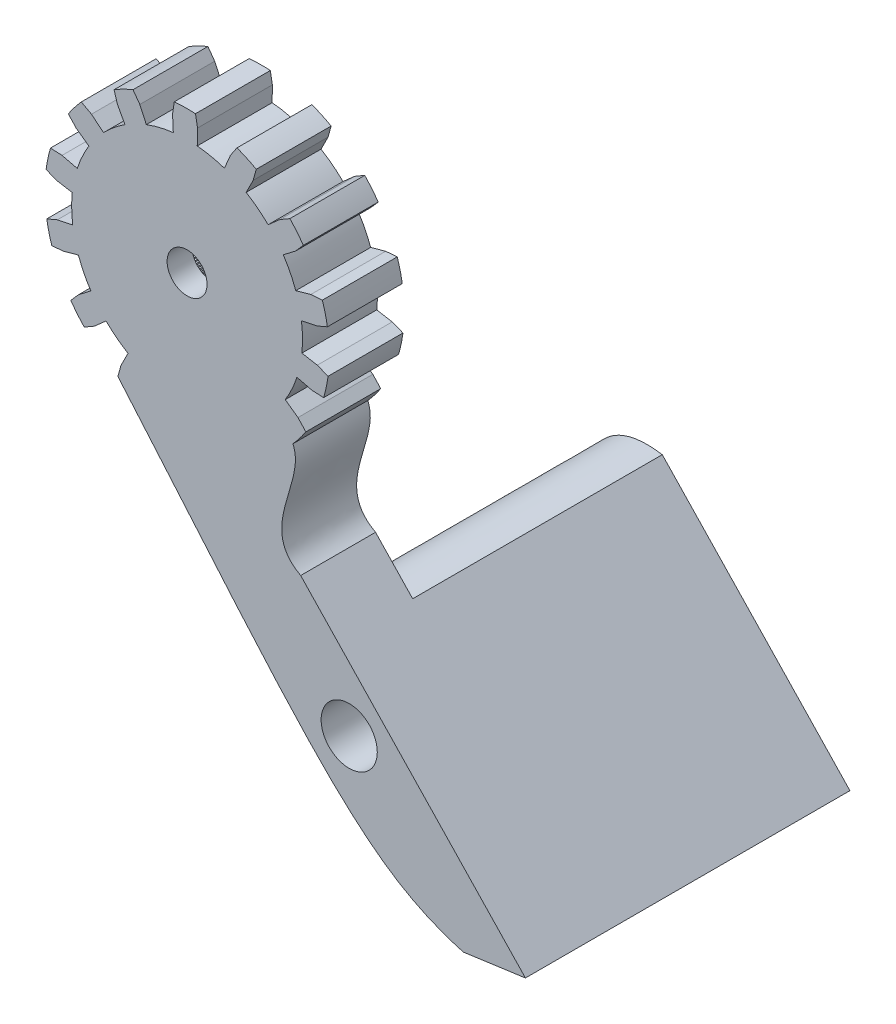
SolidWorks part; units mm, degrees
ref_plane "Front Plane" through (0, 0, 0) normal (0, 0, 1) x (1, 0, 0)
ref_plane "Top Plane" through (0, 0, 0) normal (0, 1, 0) x (1, 0, 0)
ref_plane "Right Plane" through (0, 0, 0) normal (1, 0, 0) x (0, 0, -1)
sketch "Sketch2" plane through (0, 0, 0) normal (0, 0, 1) x (1, 0, 0)
  line L0 (11.1946, 10) -> (11.1946, 10.6054) construction
  line L669 (17.6878, 7.31) -> (18.6279, 8.138)
  line L670 (18.6279, 8.138) -> (19.4304, 8.6044)
  line L671 (21.6272, -0.4657) -> (22.4922, -0.8024)
  line L672 (20.3937, -0.247) -> (21.6272, -0.4657)
  line L673 (20.3589, 1.9784) -> (21.5849, 2.2356)
  line L674 (21.5849, 2.2356) -> (22.439, 2.5991)
  line L675 (21.1094, 4.1784) -> (22.0348, 4.2505)
  line L676 (19.9032, 3.8403) -> (21.1094, 4.1784)
  line L677 (18.9062, 5.8303) -> (19.8993, 6.5939)
  line L678 (19.8993, 6.5939) -> (20.511, 7.292)
  line L679 (14.4587, -7.9329) -> (14.9822, -9.071)
  line L680 (14.9822, -9.071) -> (15.5266, -9.8227)
  line L681 (16.7705, -8.175) -> (17.0467, -9.0612)
  line L682 (16.1724, -7.0743) -> (16.7705, -8.175)
  line L683 (17.8907, -5.6595) -> (18.8561, -6.4578)
  line L684 (18.8561, -6.4578) -> (19.6729, -6.8988)
  line L685 (20.0786, -4.8746) -> (20.7119, -5.5532)
  line L686 (19.0622, -4.1424) -> (20.0786, -4.8746)
  line L687 (19.9964, -2.1222) -> (21.2126, -2.4225)
  line L688 (21.2126, -2.4225) -> (22.1398, -2.4655)
  line L689 (3.4829, -4.3861) -> (2.4899, -5.1497)
  line L690 (2.4899, -5.1497) -> (1.8781, -5.8478)
  line L691 (3.7613, -6.6939) -> (2.9588, -7.1603)
  line L692 (4.7013, -5.8658) -> (3.7613, -6.6939)
  line L693 (6.463, -7.2262) -> (5.8996, -8.3451)
  line L694 (5.8996, -8.3451) -> (5.6513, -9.2394)
  line L695 (7.7151, -9.1846) -> (7.1944, -9.953)
  line L696 (8.2027, -8.0307) -> (7.7151, -9.1846)
  line L697 (10.3802, -8.492) -> (10.3581, -9.7445)
  line L698 (10.3581, -9.7445) -> (10.5224, -10.6581)
  line L699 (12.358, -9.7133) -> (12.2223, -10.6315)
  line L700 (12.2967, -8.462) -> (12.358, -9.7133)
  line L701 (2.3105, 6.3188) -> (1.6772, 6.9974)
  line L702 (3.327, 5.5866) -> (2.3105, 6.3188)
  line L703 (2.3927, 3.5664) -> (1.1765, 3.8667)
  line L704 (1.1765, 3.8667) -> (0.2493, 3.9097)
  line L705 (0.762, 1.9099) -> (-0.103, 2.2465)
  line L706 (1.9955, 1.6912) -> (0.762, 1.9099)
  line L707 (2.0303, -0.5343) -> (0.8042, -0.7914)
  line L708 (0.8042, -0.7914) -> (-0.0498, -1.1549)
  line L709 (1.2798, -2.7343) -> (0.3543, -2.8063)
  line L710 (2.486, -2.3961) -> (1.2798, -2.7343)
  line L711 (12.009, 9.9362) -> (12.0311, 11.1887)
  line L712 (12.0311, 11.1887) -> (11.8667, 12.1023)
  line L713 (10.0311, 11.1574) -> (10.1668, 12.0757)
  line L714 (10.0924, 9.9062) -> (10.0311, 11.1574)
  line L715 (7.9305, 9.377) -> (7.4069, 10.5151)
  line L716 (7.4069, 10.5151) -> (6.8625, 11.2669)
  line L717 (5.6186, 9.6192) -> (5.3425, 10.5054)
  line L718 (6.2167, 8.5185) -> (5.6186, 9.6192)
  line L719 (4.4985, 7.1037) -> (3.533, 7.9019)
  line L720 (3.533, 7.9019) -> (2.7163, 8.343)
  line L721 (15.9262, 8.6703) -> (16.4895, 9.7892)
  line L722 (16.4895, 9.7892) -> (16.7378, 10.6836)
  line L723 (14.6741, 10.6288) -> (15.1948, 11.3972)
  line L724 (14.1864, 9.4749) -> (14.6741, 10.6288)
  arc A141 (20.511, 7.292) -> (19.4304, 8.6044) centre (11.1946, 0.7221) ccw
  arc A145 (17.6878, 7.31) -> (15.9262, 8.6703) centre (11.1946, 0.7221) ccw
  arc A149 (22.439, 2.5991) -> (22.0348, 4.2505) centre (11.1946, 0.7221) ccw
  arc A151 (22.1398, -2.4655) -> (22.4922, -0.8024) centre (11.1946, 0.7221) ccw
  arc A152 (19.6729, -6.8988) -> (20.7119, -5.5532) centre (11.1946, 0.7221) ccw
  arc A153 (15.5266, -9.8227) -> (17.0467, -9.0612) centre (11.1946, 0.7221) ccw
  arc A154 (10.5224, -10.6581) -> (12.2223, -10.6315) centre (11.1946, 0.7221) ccw
  arc A155 (5.6513, -9.2394) -> (7.1944, -9.953) centre (11.1946, 0.7221) ccw
  arc A156 (1.8781, -5.8478) -> (2.9588, -7.1603) centre (11.1946, 0.7221) ccw
  arc A157 (-0.0498, -1.1549) -> (0.3543, -2.8063) centre (11.1946, 0.7221) ccw
  arc A158 (0.2493, 3.9097) -> (-0.103, 2.2465) centre (11.1946, 0.7221) ccw
  arc A159 (2.7163, 8.343) -> (1.6772, 6.9974) centre (11.1946, 0.7221) ccw
  arc A160 (6.8625, 11.2669) -> (5.3425, 10.5054) centre (11.1946, 0.7221) ccw
  arc A161 (11.8667, 12.1023) -> (10.1668, 12.0757) centre (11.1946, 0.7221) ccw
  arc A162 (16.7378, 10.6836) -> (15.1948, 11.3972) centre (11.1946, 0.7221) ccw
  arc A163 (19.9032, 3.8403) -> (18.9062, 5.8303) centre (11.1946, 0.7221) ccw
  arc A164 (20.3937, -0.247) -> (20.3589, 1.9784) centre (11.1946, 0.7221) ccw
  arc A165 (19.0622, -4.1424) -> (19.9964, -2.1222) centre (11.1946, 0.7221) ccw
  arc A166 (16.1724, -7.0743) -> (17.8907, -5.6595) centre (11.1946, 0.7221) ccw
  arc A167 (12.2967, -8.462) -> (14.4587, -7.9329) centre (11.1946, 0.7221) ccw
  arc A168 (8.2027, -8.0307) -> (10.3802, -8.492) centre (11.1946, 0.7221) ccw
  arc A169 (4.7013, -5.8658) -> (6.463, -7.2262) centre (11.1946, 0.7221) ccw
  arc A170 (2.486, -2.3961) -> (3.4829, -4.3861) centre (11.1946, 0.7221) ccw
  arc A171 (1.9955, 1.6912) -> (2.0303, -0.5343) centre (11.1946, 0.7221) ccw
  arc A172 (3.327, 5.5866) -> (2.3927, 3.5664) centre (11.1946, 0.7221) ccw
  arc A173 (6.2167, 8.5185) -> (4.4985, 7.1037) centre (11.1946, 0.7221) ccw
  arc A174 (10.0924, 9.9062) -> (7.9305, 9.377) centre (11.1946, 0.7221) ccw
  arc A175 (14.1864, 9.4749) -> (12.009, 9.9362) centre (11.1946, 0.7221) ccw
extrude "Boss-Extrude1" add sketch "Sketch2" against normal blind 4 and the other way blind 2
sketch "Sketch3" plane through (0, 0, 2) normal (0, 0, 1) x (1, 0, 0)
  circle A0 centre (11.1946, 0) radius 3.5
  dimension "D1" = 7
extrude "Boss-Extrude2" add sketch "Sketch3" against normal blind 2
sketch "Sketch4" plane through (0, 0, 2) normal (0, 0, 1) x (1, 0, 0)
  circle A0 centre (11.1946, 0.7221) radius 4.295 construction
sketch "Sketch5" plane through (0, 0, 2) normal (0, 0, 1) x (1, 0, 0)
  line L0 (10.0276, -11.444) -> (15.4878, -11.444) construction
  line L1 (4.4176, 11.5) -> (18.1778, 11.5) construction
  line L5 (20.2959, -15.7283) -> (38.3061, -34.6532)
  line L7 (33.3336, -35.343) -> (38.3061, -34.6532)
  line L25 (15.9262, 8.6703) -> (16.4895, 9.7892)
  line L35 (3.4829, -4.3861) -> (2.4899, -5.1497)
  line L45 (15.1948, 11.3972) -> (14.6741, 10.6288)
  line L55 (14.6741, 10.6288) -> (14.1864, 9.4749)
  line L98 (22.0348, 4.2505) -> (21.1094, 4.1784)
  line L102 (12.009, 9.9362) -> (12.0311, 11.1887)
  line L104 (14.9822, -9.071) -> (15.5266, -9.8227)
  line L105 (14.9822, -9.071) -> (15.5266, -9.8227)
  line L110 (2.4899, -5.1497) -> (1.8781, -5.8478)
  line L114 (5.8996, -8.3451) -> (5.6513, -9.2394)
  line L124 (2.3927, 3.5664) -> (1.1765, 3.8667)
  line L126 (1.1765, 3.8667) -> (0.2493, 3.9097)
  line L130 (0.8042, -0.7914) -> (-0.0498, -1.1549)
  line L140 (5.3425, 10.5054) -> (5.6186, 9.6192)
  line L146 (16.4895, 9.7892) -> (16.7378, 10.6836)
  line L153 (12.0311, 11.1887) -> (11.8667, 12.1023)
  line L157 (10.1668, 12.0757) -> (10.0311, 11.1574)
  line L161 (10.0311, 11.1574) -> (10.0924, 9.9062)
  line L196 (7.9305, 9.377) -> (7.4069, 10.5151)
  line L198 (7.4069, 10.5151) -> (6.8625, 11.2669)
  line L200 (5.6186, 9.6192) -> (6.2167, 8.5185)
  line L202 (4.4985, 7.1037) -> (3.533, 7.9019)
  line L204 (3.533, 7.9019) -> (2.7163, 8.343)
  line L206 (1.6772, 6.9974) -> (2.3105, 6.3188)
  line L208 (2.3105, 6.3188) -> (3.327, 5.5866)
  line L210 (-0.103, 2.2465) -> (0.762, 1.9099)
  line L212 (0.762, 1.9099) -> (1.9955, 1.6912)
  line L214 (2.0303, -0.5343) -> (0.8042, -0.7914)
  line L216 (0.3543, -2.8063) -> (1.2798, -2.7343)
  line L218 (1.2798, -2.7343) -> (2.486, -2.3961)
  line L220 (2.9588, -7.1603) -> (3.7613, -6.6939)
  line L222 (3.7613, -6.6939) -> (4.7013, -5.8658)
  line L224 (6.463, -7.2262) -> (5.8996, -8.3451)
  line L226 (7.1944, -9.953) -> (7.7151, -9.1846)
  line L227 (7.1944, -9.953) -> (7.7151, -9.1846)
  line L228 (7.7151, -9.1846) -> (8.2027, -8.0307)
  line L229 (7.7151, -9.1846) -> (8.2027, -8.0307)
  line L230 (10.3802, -8.492) -> (10.3581, -9.7445)
  line L231 (10.3802, -8.492) -> (10.3581, -9.7445)
  line L232 (10.3581, -9.7445) -> (10.5224, -10.6581)
  line L233 (10.3581, -9.7445) -> (10.5224, -10.6581)
  line L234 (12.2223, -10.6315) -> (12.358, -9.7133)
  line L235 (12.2223, -10.6315) -> (12.358, -9.7133)
  line L236 (12.358, -9.7133) -> (12.2967, -8.462)
  line L237 (12.358, -9.7133) -> (12.2967, -8.462)
  line L238 (14.4587, -7.9329) -> (14.9822, -9.071)
  line L239 (14.4587, -7.9329) -> (14.9822, -9.071)
  line L240 (17.0467, -9.0612) -> (16.7705, -8.175)
  line L241 (17.0467, -9.0612) -> (16.7705, -8.175)
  line L242 (16.7705, -8.175) -> (16.1724, -7.0743)
  line L243 (16.7705, -8.175) -> (16.1724, -7.0743)
  line L244 (17.8907, -5.6595) -> (18.8561, -6.4578)
  line L245 (17.8907, -5.6595) -> (18.8561, -6.4578)
  line L246 (18.8561, -6.4578) -> (19.6729, -6.8988)
  line L247 (18.8561, -6.4578) -> (19.6729, -6.8988)
  line L248 (20.7119, -5.5532) -> (20.0786, -4.8746)
  line L250 (20.0786, -4.8746) -> (19.0622, -4.1424)
  line L252 (19.9964, -2.1222) -> (21.2126, -2.4225)
  line L254 (21.2126, -2.4225) -> (22.1398, -2.4655)
  line L256 (22.4922, -0.8024) -> (21.6272, -0.4657)
  line L258 (21.6272, -0.4657) -> (20.3937, -0.247)
  line L260 (20.3589, 1.9784) -> (21.5849, 2.2356)
  line L262 (21.5849, 2.2356) -> (22.439, 2.5991)
  line L264 (21.1094, 4.1784) -> (19.9032, 3.8403)
  line L266 (18.9062, 5.8303) -> (19.8993, 6.5939)
  line L268 (19.8993, 6.5939) -> (20.511, 7.292)
  line L270 (19.4304, 8.6044) -> (18.6279, 8.138)
  line L272 (18.6279, 8.138) -> (17.6878, 7.31)
  arc A14 (17.6878, 7.31) -> (15.9262, 8.6703) centre (11.1946, 0.7221) ccw
  arc A36 (16.7378, 10.6836) -> (15.1948, 11.3972) centre (11.1946, 0.7221) ccw
  arc A44 (14.1864, 9.4749) -> (12.009, 9.9362) centre (11.1946, 0.7221) ccw
  arc A52 (11.8667, 12.1023) -> (10.1668, 12.0757) centre (11.1946, 0.7221) ccw
  arc A98 (10.0924, 9.9062) -> (7.9305, 9.377) centre (11.1946, 0.7221) ccw
  arc A100 (6.8625, 11.2669) -> (5.3425, 10.5054) centre (11.1946, 0.7221) ccw
  arc A102 (6.2167, 8.5185) -> (4.4985, 7.1037) centre (11.1946, 0.7221) ccw
  arc A104 (2.7163, 8.343) -> (1.6772, 6.9974) centre (11.1946, 0.7221) ccw
  arc A106 (3.327, 5.5866) -> (2.3927, 3.5664) centre (11.1946, 0.7221) ccw
  arc A108 (0.2493, 3.9097) -> (-0.103, 2.2465) centre (11.1946, 0.7221) ccw
  arc A110 (1.9955, 1.6912) -> (2.0303, -0.5343) centre (11.1946, 0.7221) ccw
  arc A112 (-0.0498, -1.1549) -> (0.3543, -2.8063) centre (11.1946, 0.7221) ccw
  arc A114 (2.486, -2.3961) -> (3.4829, -4.3861) centre (11.1946, 0.7221) ccw
  arc A116 (1.8781, -5.8478) -> (2.9588, -7.1603) centre (11.1946, 0.7221) ccw
  arc A118 (4.7013, -5.8658) -> (6.463, -7.2262) centre (11.1946, 0.7221) ccw
  arc A120 (5.6513, -9.2394) -> (7.1944, -9.953) centre (11.1946, 0.7221) ccw
  arc A121 (5.6513, -9.2394) -> (7.1944, -9.953) centre (11.1946, 0.7221) ccw
  arc A122 (8.2027, -8.0307) -> (10.3802, -8.492) centre (11.1946, 0.7221) ccw
  arc A123 (8.2027, -8.0307) -> (10.3802, -8.492) centre (11.1946, 0.7221) ccw
  arc A124 (10.5224, -10.6581) -> (12.2223, -10.6315) centre (11.1946, 0.7221) ccw
  arc A125 (10.5224, -10.6581) -> (12.2223, -10.6315) centre (11.1946, 0.7221) ccw
  arc A126 (12.2967, -8.462) -> (14.4587, -7.9329) centre (11.1946, 0.7221) ccw
  arc A127 (12.2967, -8.462) -> (14.4587, -7.9329) centre (11.1946, 0.7221) ccw
  arc A128 (15.5266, -9.8227) -> (17.0467, -9.0612) centre (11.1946, 0.7221) ccw
  arc A129 (15.5266, -9.8227) -> (17.0467, -9.0612) centre (11.1946, 0.7221) ccw
  arc A130 (16.1724, -7.0743) -> (17.8907, -5.6595) centre (11.1946, 0.7221) ccw
  arc A131 (16.1724, -7.0743) -> (17.8907, -5.6595) centre (11.1946, 0.7221) ccw
  arc A132 (19.6729, -6.8988) -> (20.7119, -5.5532) centre (11.1946, 0.7221) ccw
  arc A134 (19.0622, -4.1424) -> (19.9964, -2.1222) centre (11.1946, 0.7221) ccw
  arc A136 (22.1398, -2.4655) -> (22.4922, -0.8024) centre (11.1946, 0.7221) ccw
  arc A138 (20.3937, -0.247) -> (20.3589, 1.9784) centre (11.1946, 0.7221) ccw
  arc A140 (22.439, 2.5991) -> (22.0348, 4.2505) centre (11.1946, 0.7221) ccw
  arc A142 (19.9032, 3.8403) -> (18.9062, 5.8303) centre (11.1946, 0.7221) ccw
  arc A144 (20.511, 7.292) -> (19.4304, 8.6044) centre (11.1946, 0.7221) ccw
  spline S0 degree 3 poles (19.6729, -6.8988) (20.7965, -9.2961) (16.694, -13.7781) (20.2959, -15.7283) knots 0 0 0 0 1 1 1 1
  spline S1 degree 3 poles (33.3336, -35.343) (25.4692, -33.1533) (21.4591, -27.7657) (5.6513, -9.2394) knots 0.222416 0.222416 0.222416 0.222416 1 1 1 1
  dimension "D1" = 0
extrude "Boss-Extrude3" add sketch "Sketch5" against normal up to surface (6 mm away) up to face at (11.1946, 0.7221, -4)
sketch "Sketch6" plane through (0, 0, -4) normal (0, 0, -1) x (-1, 0, 0)
  line L1 (-38.3061, -34.6532) -> (-20.2959, -15.7283) construction
  line L2 (-38.3061, -34.6532) -> (-23.2711, -18.8546)
  line L24 (-2.4899, -5.1497) -> (-3.4829, -4.3861)
  line L32 (-20.2959, -15.7283) -> (-38.3061, -34.6532)
  line L86 (-38.3061, -34.6532) -> (-33.3336, -35.343)
  line L88 (-38.3061, -34.6532) -> (-33.3336, -35.343)
  line L141 (-16.7378, 10.6836) -> (-16.4895, 9.7892)
  line L147 (-5.6186, 9.6192) -> (-5.3425, 10.5054)
  line L157 (0.0498, -1.1549) -> (-0.8042, -0.7914)
  line L161 (-0.2493, 3.9097) -> (-1.1765, 3.8667)
  line L163 (-1.1765, 3.8667) -> (-2.3927, 3.5664)
  line L173 (-5.6513, -9.2394) -> (-5.8996, -8.3451)
  line L177 (-1.8781, -5.8478) -> (-2.4899, -5.1497)
  line L206 (-21.1094, 4.1784) -> (-22.0348, 4.2505)
  line L208 (-17.6878, 7.31) -> (-18.6279, 8.138)
  line L210 (-18.6279, 8.138) -> (-19.4304, 8.6044)
  line L212 (-20.511, 7.292) -> (-19.8993, 6.5939)
  line L214 (-19.8993, 6.5939) -> (-18.9062, 5.8303)
  line L216 (-19.9032, 3.8403) -> (-21.1094, 4.1784)
  line L218 (-22.439, 2.5991) -> (-21.5849, 2.2356)
  line L220 (-21.5849, 2.2356) -> (-20.3589, 1.9784)
  line L222 (-20.3937, -0.247) -> (-21.6272, -0.4657)
  line L224 (-21.6272, -0.4657) -> (-22.4922, -0.8024)
  line L226 (-22.1398, -2.4655) -> (-21.2126, -2.4225)
  line L228 (-21.2126, -2.4225) -> (-19.9964, -2.1222)
  line L230 (-19.0622, -4.1424) -> (-20.0786, -4.8746)
  line L232 (-20.0786, -4.8746) -> (-20.7119, -5.5532)
  line L256 (-5.8996, -8.3451) -> (-6.463, -7.2262)
  line L258 (-4.7013, -5.8658) -> (-3.7613, -6.6939)
  line L260 (-3.7613, -6.6939) -> (-2.9588, -7.1603)
  line L262 (-2.486, -2.3961) -> (-1.2798, -2.7343)
  line L264 (-1.2798, -2.7343) -> (-0.3543, -2.8063)
  line L266 (-0.8042, -0.7914) -> (-2.0303, -0.5343)
  line L268 (-1.9955, 1.6912) -> (-0.762, 1.9099)
  line L270 (-0.762, 1.9099) -> (0.103, 2.2465)
  line L272 (-3.327, 5.5866) -> (-2.3105, 6.3188)
  line L274 (-2.3105, 6.3188) -> (-1.6772, 6.9974)
  line L276 (-2.7163, 8.343) -> (-3.533, 7.9019)
  line L278 (-3.533, 7.9019) -> (-4.4985, 7.1037)
  line L280 (-6.2167, 8.5185) -> (-5.6186, 9.6192)
  line L282 (-6.8625, 11.2669) -> (-7.4069, 10.5151)
  line L284 (-7.4069, 10.5151) -> (-7.9305, 9.377)
  line L286 (-10.0924, 9.9062) -> (-10.0311, 11.1574)
  line L288 (-10.0311, 11.1574) -> (-10.1668, 12.0757)
  line L290 (-11.8667, 12.1023) -> (-12.0311, 11.1887)
  line L292 (-12.0311, 11.1887) -> (-12.009, 9.9362)
  line L294 (-14.1864, 9.4749) -> (-14.6741, 10.6288)
  line L296 (-14.6741, 10.6288) -> (-15.1948, 11.3972)
  line L298 (-16.4895, 9.7892) -> (-15.9262, 8.6703)
  arc A44 (-15.9262, 8.6703) -> (-17.6878, 7.31) centre (-11.1946, 0.7221) ccw
  arc A85 (-19.4304, 8.6044) -> (-20.511, 7.292) centre (-11.1946, 0.7221) ccw
  arc A87 (-18.9062, 5.8303) -> (-19.9032, 3.8403) centre (-11.1946, 0.7221) ccw
  arc A89 (-22.0348, 4.2505) -> (-22.439, 2.5991) centre (-11.1946, 0.7221) ccw
  arc A91 (-20.3589, 1.9784) -> (-20.3937, -0.247) centre (-11.1946, 0.7221) ccw
  arc A93 (-22.4922, -0.8024) -> (-22.1398, -2.4655) centre (-11.1946, 0.7221) ccw
  arc A95 (-19.9964, -2.1222) -> (-19.0622, -4.1424) centre (-11.1946, 0.7221) ccw
  arc A97 (-20.7119, -5.5532) -> (-19.6729, -6.8988) centre (-11.1946, 0.7221) ccw
  arc A111 (-6.463, -7.2262) -> (-4.7013, -5.8658) centre (-11.1946, 0.7221) ccw
  arc A113 (-2.9588, -7.1603) -> (-1.8781, -5.8478) centre (-11.1946, 0.7221) ccw
  arc A115 (-3.4829, -4.3861) -> (-2.486, -2.3961) centre (-11.1946, 0.7221) ccw
  arc A117 (-0.3543, -2.8063) -> (0.0498, -1.1549) centre (-11.1946, 0.7221) ccw
  arc A119 (-2.0303, -0.5343) -> (-1.9955, 1.6912) centre (-11.1946, 0.7221) ccw
  arc A121 (0.103, 2.2465) -> (-0.2493, 3.9097) centre (-11.1946, 0.7221) ccw
  arc A123 (-2.3927, 3.5664) -> (-3.327, 5.5866) centre (-11.1946, 0.7221) ccw
  arc A125 (-1.6772, 6.9974) -> (-2.7163, 8.343) centre (-11.1946, 0.7221) ccw
  arc A127 (-4.4985, 7.1037) -> (-6.2167, 8.5185) centre (-11.1946, 0.7221) ccw
  arc A129 (-5.3425, 10.5054) -> (-6.8625, 11.2669) centre (-11.1946, 0.7221) ccw
  arc A131 (-7.9305, 9.377) -> (-10.0924, 9.9062) centre (-11.1946, 0.7221) ccw
  arc A133 (-10.1668, 12.0757) -> (-11.8667, 12.1023) centre (-11.1946, 0.7221) ccw
  arc A135 (-12.009, 9.9362) -> (-14.1864, 9.4749) centre (-11.1946, 0.7221) ccw
  arc A137 (-15.1948, 11.3972) -> (-16.7378, 10.6836) centre (-11.1946, 0.7221) ccw
  spline S1 degree 3 poles (3095.3145, 2513.7316) (-3152.5377, -2225.239) (3257.3003, 1866.3624) (-3659.2624, -1714.1694) knots -3.676611 -3.676611 -3.676611 -3.676611 5.530605 5.530605 5.530605 5.530605 only from (-5.6513, -9.2394) to (-33.3336, -35.343) construction
  spline S3 degree 3 poles (-17.1172, -22.6359) (-24.2126, -30.7109) (-27.8289, -33.8103) (-33.3336, -35.343) knots 0.455733 0.455733 0.455733 0.455733 1 1 1 1
  spline S4 degree 2 poles (-17.1172, -22.6359) (-18.6565, -18.1405) (-23.2711, -18.8546) knots 0 0 0 1 1 1
  spline S6 degree 3 poles (928.9961, -323.1558) (-986.7592, 351.2189) (950.6356, -365.5096) (-975.1186, 281.4128) knots -3.799895 -3.799895 -3.799895 -3.799895 4.619147 4.619147 4.619147 4.619147 only from (-19.6729, -6.8988) to (-20.2959, -15.7283)
  spline S7 degree 3 poles (-969.9828, -385.6106) (744.6842, 387.8248) (-748.6875, -572.1614) (734.9995, 662.636) knots -2.545715 -2.545715 -2.545715 -2.545715 3.160411 3.160411 3.160411 3.160411 only from (-33.3336, -35.343) to (-5.6513, -9.2394)
  dimension "D1" = 0
extrude "Boss-Extrude4" add sketch "Sketch6" along normal blind 20
sketch "Sketch7" plane through (0, 0, -4) normal (0, 0, -1) x (-1, 0, 0)
  line L200 (-9.7843, 3.3038) -> (-9.9297, 3.2201)
  line L201 (-9.7763, 3.1362) -> (-9.7843, 3.3038)
  line L202 (-9.6259, 3.2107) -> (-9.7763, 3.1362)
  line L203 (-9.6285, 3.0429) -> (-9.6259, 3.2107)
  line L204 (-9.4737, 3.1077) -> (-9.6285, 3.0429)
  line L205 (-9.4868, 2.9405) -> (-9.4737, 3.1077)
  line L206 (-9.3283, 2.9955) -> (-9.4868, 2.9405)
  line L207 (-9.3518, 2.8293) -> (-9.3283, 2.9955)
  line L208 (-9.1901, 2.8743) -> (-9.3518, 2.8293)
  line L209 (-9.2241, 2.7099) -> (-9.1901, 2.8743)
  line L210 (-9.0599, 2.7446) -> (-9.2241, 2.7099)
  line L211 (-9.1041, 2.5828) -> (-9.0599, 2.7446)
  line L212 (-8.9381, 2.6071) -> (-9.1041, 2.5828)
  line L213 (-8.9923, 2.4483) -> (-8.9381, 2.6071)
  line L214 (-8.8251, 2.4622) -> (-8.9923, 2.4483)
  line L215 (-8.8892, 2.3071) -> (-8.8251, 2.4622)
  line L216 (-8.7215, 2.3104) -> (-8.8892, 2.3071)
  line L217 (-8.7952, 2.1597) -> (-8.7215, 2.3104)
  line L218 (-8.6276, 2.1525) -> (-8.7952, 2.1597)
  line L219 (-8.7106, 2.0067) -> (-8.6276, 2.1525)
  line L220 (-8.5438, 1.9889) -> (-8.7106, 2.0067)
  line L221 (-8.6358, 1.8487) -> (-8.5438, 1.9889)
  line L222 (-8.4704, 1.8205) -> (-8.6358, 1.8487)
  line L223 (-8.571, 1.6862) -> (-8.4704, 1.8205)
  line L224 (-8.4077, 1.6477) -> (-8.571, 1.6862)
  line L225 (-8.5166, 1.5201) -> (-8.4077, 1.6477)
  line L226 (-8.3561, 1.4714) -> (-8.5166, 1.5201)
  line L227 (-8.4727, 1.3508) -> (-8.3561, 1.4714)
  line L228 (-8.3156, 1.2922) -> (-8.4727, 1.3508)
  line L229 (-8.4396, 1.1792) -> (-8.3156, 1.2922)
  line L230 (-8.2864, 1.1108) -> (-8.4396, 1.1792)
  line L231 (-8.4173, 1.0058) -> (-8.2864, 1.1108)
  line L232 (-8.2687, 0.9279) -> (-8.4173, 1.0058)
  line L233 (-8.4059, 0.8313) -> (-8.2687, 0.9279)
  line L234 (-8.2625, 0.7442) -> (-8.4059, 0.8313)
  line L235 (-8.4055, 0.6565) -> (-8.2625, 0.7442)
  line L236 (-8.2678, 0.5605) -> (-8.4055, 0.6565)
  line L237 (-8.416, 0.4819) -> (-8.2678, 0.5605)
  line L238 (-8.2847, 0.3776) -> (-8.416, 0.4819)
  line L239 (-8.4375, 0.3084) -> (-8.2847, 0.3776)
  line L240 (-8.313, 0.196) -> (-8.4375, 0.3084)
  line L241 (-8.4699, 0.1366) -> (-8.313, 0.196)
  line L242 (-8.3527, 0.0166) -> (-8.4699, 0.1366)
  line L243 (-8.513, -0.0328) -> (-8.3527, 0.0166)
  line L244 (-8.4035, -0.16) -> (-8.513, -0.0328)
  line L245 (-8.5666, -0.1993) -> (-8.4035, -0.16)
  line L246 (-8.4653, -0.333) -> (-8.5666, -0.1993)
  line L247 (-8.6306, -0.362) -> (-8.4653, -0.333)
  line L248 (-8.5379, -0.5018) -> (-8.6306, -0.362)
  line L249 (-8.7047, -0.5203) -> (-8.5379, -0.5018)
  line L250 (-8.621, -0.6657) -> (-8.7047, -0.5203)
  line L251 (-8.7886, -0.6738) -> (-8.621, -0.6657)
  line L252 (-8.7141, -0.8241) -> (-8.7886, -0.6738)
  line L253 (-8.8819, -0.8216) -> (-8.7141, -0.8241)
  line L254 (-8.8171, -0.9763) -> (-8.8819, -0.8216)
  line L255 (-8.9843, -0.9633) -> (-8.8171, -0.9763)
  line L256 (-8.9293, -1.1218) -> (-8.9843, -0.9633)
  line L257 (-9.0955, -1.0983) -> (-8.9293, -1.1218)
  line L258 (-9.0505, -1.2599) -> (-9.0955, -1.0983)
  line L259 (-9.2148, -1.226) -> (-9.0505, -1.2599)
  line L260 (-9.1802, -1.3901) -> (-9.2148, -1.226)
  line L261 (-9.342, -1.346) -> (-9.1802, -1.3901)
  line L262 (-9.3177, -1.512) -> (-9.342, -1.346)
  line L263 (-9.4765, -1.4577) -> (-9.3177, -1.512)
  line L264 (-9.4626, -1.6249) -> (-9.4765, -1.4577)
  line L265 (-9.6177, -1.5608) -> (-9.4626, -1.6249)
  line L266 (-9.6144, -1.7286) -> (-9.6177, -1.5608)
  line L267 (-9.7651, -1.6549) -> (-9.6144, -1.7286)
  line L268 (-9.7723, -1.8225) -> (-9.7651, -1.6549)
  line L269 (-9.9181, -1.7395) -> (-9.7723, -1.8225)
  line L270 (-9.9358, -1.9063) -> (-9.9181, -1.7395)
  line L271 (-10.0761, -1.8143) -> (-9.9358, -1.9063)
  line L272 (-10.1043, -1.9797) -> (-10.0761, -1.8143)
  line L273 (-10.2385, -1.879) -> (-10.1043, -1.9797)
  line L274 (-10.2771, -2.0423) -> (-10.2385, -1.879)
  line L275 (-10.4047, -1.9334) -> (-10.2771, -2.0423)
  line L276 (-10.4534, -2.094) -> (-10.4047, -1.9334)
  line L277 (-10.5739, -1.9773) -> (-10.4534, -2.094)
  line L278 (-10.6326, -2.1345) -> (-10.5739, -1.9773)
  line L279 (-10.7456, -2.0105) -> (-10.6326, -2.1345)
  line L280 (-10.814, -2.1637) -> (-10.7456, -2.0105)
  line L281 (-10.919, -2.0328) -> (-10.814, -2.1637)
  line L282 (-10.9969, -2.1814) -> (-10.919, -2.0328)
  line L283 (-11.0935, -2.0442) -> (-10.9969, -2.1814)
  line L284 (-11.1806, -2.1876) -> (-11.0935, -2.0442)
  line L285 (-11.2683, -2.0446) -> (-11.1806, -2.1876)
  line L286 (-11.3643, -2.1822) -> (-11.2683, -2.0446)
  line L287 (-11.4429, -2.034) -> (-11.3643, -2.1822)
  line L288 (-11.5472, -2.1654) -> (-11.4429, -2.034)
  line L289 (-11.6164, -2.0125) -> (-11.5472, -2.1654)
  line L290 (-11.7288, -2.1371) -> (-11.6164, -2.0125)
  line L291 (-11.7882, -1.9802) -> (-11.7288, -2.1371)
  line L292 (-11.9082, -2.0974) -> (-11.7882, -1.9802)
  line L293 (-11.9576, -1.9371) -> (-11.9082, -2.0974)
  line L294 (-12.0848, -2.0465) -> (-11.9576, -1.9371)
  line L295 (-12.1241, -1.8834) -> (-12.0848, -2.0465)
  line L296 (-12.2578, -1.9847) -> (-12.1241, -1.8834)
  line L297 (-12.2868, -1.8194) -> (-12.2578, -1.9847)
  line L298 (-12.4266, -1.9121) -> (-12.2868, -1.8194)
  line L299 (-12.4451, -1.7454) -> (-12.4266, -1.9121)
  line L300 (-12.5905, -1.8291) -> (-12.4451, -1.7454)
  line L301 (-12.5985, -1.6615) -> (-12.5905, -1.8291)
  line L302 (-12.7489, -1.7359) -> (-12.5985, -1.6615)
  line L303 (-12.7464, -1.5682) -> (-12.7489, -1.7359)
  line L304 (-12.9011, -1.633) -> (-12.7464, -1.5682)
  line L305 (-12.8881, -1.4657) -> (-12.9011, -1.633)
  line L306 (-13.0466, -1.5207) -> (-12.8881, -1.4657)
  line L307 (-13.0231, -1.3546) -> (-13.0466, -1.5207)
  line L308 (-13.1847, -1.3995) -> (-13.0231, -1.3546)
  line L309 (-13.1508, -1.2352) -> (-13.1847, -1.3995)
  line L310 (-13.3149, -1.2699) -> (-13.1508, -1.2352)
  line L311 (-13.2708, -1.108) -> (-13.3149, -1.2699)
  line L312 (-13.4368, -1.1323) -> (-13.2708, -1.108)
  line L313 (-13.3825, -0.9736) -> (-13.4368, -1.1323)
  line L314 (-13.5497, -0.9874) -> (-13.3825, -0.9736)
  line L315 (-13.4856, -0.8324) -> (-13.5497, -0.9874)
  line L316 (-13.6534, -0.8357) -> (-13.4856, -0.8324)
  line L317 (-13.5797, -0.685) -> (-13.6534, -0.8357)
  line L318 (-13.7473, -0.6777) -> (-13.5797, -0.685)
  line L319 (-13.6643, -0.5319) -> (-13.7473, -0.6777)
  line L320 (-13.8311, -0.5142) -> (-13.6643, -0.5319)
  line L321 (-13.7391, -0.3739) -> (-13.8311, -0.5142)
  line L322 (-13.9045, -0.3457) -> (-13.7391, -0.3739)
  line L323 (-13.8038, -0.2115) -> (-13.9045, -0.3457)
  line L324 (-13.9671, -0.173) -> (-13.8038, -0.2115)
  line L325 (-13.8582, -0.0453) -> (-13.9671, -0.173)
  line L326 (-14.0188, 0.0033) -> (-13.8582, -0.0453)
  line L327 (-13.9021, 0.1239) -> (-14.0188, 0.0033)
  line L328 (-14.0593, 0.1826) -> (-13.9021, 0.1239)
  line L329 (-13.9353, 0.2956) -> (-14.0593, 0.1826)
  line L330 (-14.0885, 0.364) -> (-13.9353, 0.2956)
  line L331 (-13.9576, 0.469) -> (-14.0885, 0.364)
  line L332 (-14.1062, 0.5469) -> (-13.9576, 0.469)
  line L333 (-13.969, 0.6434) -> (-14.1062, 0.5469)
  line L334 (-14.1124, 0.7305) -> (-13.969, 0.6434)
  line L335 (-13.9694, 0.8183) -> (-14.1124, 0.7305)
  line L336 (-14.107, 0.9142) -> (-13.9694, 0.8183)
  line L337 (-13.9588, 0.9928) -> (-14.107, 0.9142)
  line L338 (-14.0902, 1.0972) -> (-13.9588, 0.9928)
  line L339 (-13.9373, 1.1663) -> (-14.0902, 1.0972)
  line L340 (-14.0619, 1.2787) -> (-13.9373, 1.1663)
  line L341 (-13.9049, 1.3381) -> (-14.0619, 1.2787)
  line L342 (-14.0222, 1.4582) -> (-13.9049, 1.3381)
  line L343 (-13.8619, 1.5076) -> (-14.0222, 1.4582)
  line L344 (-13.9713, 1.6347) -> (-13.8619, 1.5076)
  line L345 (-13.8082, 1.674) -> (-13.9713, 1.6347)
  line L346 (-13.9095, 1.8078) -> (-13.8082, 1.674)
  line L347 (-13.7442, 1.8367) -> (-13.9095, 1.8078)
  line L348 (-13.8369, 1.9766) -> (-13.7442, 1.8367)
  line L349 (-13.6702, 1.9951) -> (-13.8369, 1.9766)
  line L350 (-13.7539, 2.1405) -> (-13.6702, 1.9951)
  line L351 (-13.5863, 2.1485) -> (-13.7539, 2.1405)
  line L352 (-13.6607, 2.2989) -> (-13.5863, 2.1485)
  line L353 (-13.493, 2.2963) -> (-13.6607, 2.2989)
  line L354 (-13.5578, 2.4511) -> (-13.493, 2.2963)
  line L355 (-13.3905, 2.438) -> (-13.5578, 2.4511)
  line L356 (-13.4455, 2.5965) -> (-13.3905, 2.438)
  line L357 (-13.2794, 2.573) -> (-13.4455, 2.5965)
  line L358 (-13.3243, 2.7347) -> (-13.2794, 2.573)
  line L359 (-13.16, 2.7007) -> (-13.3243, 2.7347)
  line L360 (-13.1947, 2.8649) -> (-13.16, 2.7007)
  line L361 (-13.0328, 2.8207) -> (-13.1947, 2.8649)
  line L362 (-13.0571, 2.9867) -> (-13.0328, 2.8207)
  line L363 (-12.8984, 2.9325) -> (-13.0571, 2.9867)
  line L364 (-12.9122, 3.0997) -> (-12.8984, 2.9325)
  line L365 (-12.7572, 3.0356) -> (-12.9122, 3.0997)
  line L366 (-12.7605, 3.2033) -> (-12.7572, 3.0356)
  line L367 (-12.6098, 3.1296) -> (-12.7605, 3.2033)
  line L368 (-12.6025, 3.2972) -> (-12.6098, 3.1296)
  line L369 (-12.4567, 3.2142) -> (-12.6025, 3.2972)
  line L370 (-12.439, 3.381) -> (-12.4567, 3.2142)
  line L371 (-12.2987, 3.289) -> (-12.439, 3.381)
  line L372 (-12.2705, 3.4544) -> (-12.2987, 3.289)
  line L373 (-12.1363, 3.3538) -> (-12.2705, 3.4544)
  line L374 (-12.0978, 3.5171) -> (-12.1363, 3.3538)
  line L375 (-11.9701, 3.4082) -> (-12.0978, 3.5171)
  line L376 (-11.9215, 3.5687) -> (-11.9701, 3.4082)
  line L377 (-11.8009, 3.4521) -> (-11.9215, 3.5687)
  line L378 (-11.7422, 3.6092) -> (-11.8009, 3.4521)
  line L379 (-11.6292, 3.4852) -> (-11.7422, 3.6092)
  line L380 (-11.5608, 3.6384) -> (-11.6292, 3.4852)
  line L381 (-11.4558, 3.5075) -> (-11.5608, 3.6384)
  line L382 (-11.3779, 3.6561) -> (-11.4558, 3.5075)
  line L383 (-11.2814, 3.5189) -> (-11.3779, 3.6561)
  line L384 (-11.1943, 3.6623) -> (-11.2814, 3.5189)
  line L385 (-11.1065, 3.5193) -> (-11.1943, 3.6623)
  line L386 (-11.0106, 3.657) -> (-11.1065, 3.5193)
  line L387 (-10.932, 3.5088) -> (-11.0106, 3.657)
  line L388 (-10.8276, 3.6401) -> (-10.932, 3.5088)
  line L389 (-10.7585, 3.4873) -> (-10.8276, 3.6401)
  line L390 (-10.6461, 3.6118) -> (-10.7585, 3.4873)
  line L391 (-10.5867, 3.4549) -> (-10.6461, 3.6118)
  line L392 (-10.4666, 3.5721) -> (-10.5867, 3.4549)
  line L393 (-10.4172, 3.4118) -> (-10.4666, 3.5721)
  line L394 (-10.2901, 3.5213) -> (-10.4172, 3.4118)
  line L395 (-10.2508, 3.3582) -> (-10.2901, 3.5213)
  line L396 (-10.117, 3.4594) -> (-10.2508, 3.3582)
  line L397 (-10.0881, 3.2942) -> (-10.117, 3.4594)
  line L398 (-9.9482, 3.3869) -> (-10.0881, 3.2942)
  line L399 (-9.9297, 3.2201) -> (-9.9482, 3.3869)
  line L400 (-9.7843, 3.3038) -> (-9.9297, 3.2201)
  line L401 (-9.7763, 3.1362) -> (-9.7843, 3.3038)
  line L402 (-9.6259, 3.2107) -> (-9.7763, 3.1362)
  line L403 (-9.6285, 3.0429) -> (-9.6259, 3.2107)
  line L404 (-9.4737, 3.1077) -> (-9.6285, 3.0429)
  line L405 (-9.4868, 2.9405) -> (-9.4737, 3.1077)
  line L406 (-9.3283, 2.9955) -> (-9.4868, 2.9405)
  line L407 (-9.3518, 2.8293) -> (-9.3283, 2.9955)
  line L408 (-9.1901, 2.8743) -> (-9.3518, 2.8293)
  line L409 (-9.2241, 2.7099) -> (-9.1901, 2.8743)
  line L410 (-9.0599, 2.7446) -> (-9.2241, 2.7099)
  line L411 (-9.1041, 2.5828) -> (-9.0599, 2.7446)
  line L412 (-8.9381, 2.6071) -> (-9.1041, 2.5828)
  line L413 (-8.9923, 2.4483) -> (-8.9381, 2.6071)
  line L414 (-8.8251, 2.4622) -> (-8.9923, 2.4483)
  line L415 (-8.8892, 2.3071) -> (-8.8251, 2.4622)
  line L416 (-8.7215, 2.3104) -> (-8.8892, 2.3071)
  line L417 (-8.7952, 2.1597) -> (-8.7215, 2.3104)
  line L418 (-8.6276, 2.1525) -> (-8.7952, 2.1597)
  line L419 (-8.7106, 2.0067) -> (-8.6276, 2.1525)
  line L420 (-8.5438, 1.9889) -> (-8.7106, 2.0067)
  line L421 (-8.6358, 1.8487) -> (-8.5438, 1.9889)
  line L422 (-8.4704, 1.8205) -> (-8.6358, 1.8487)
  line L423 (-8.571, 1.6862) -> (-8.4704, 1.8205)
  line L424 (-8.4077, 1.6477) -> (-8.571, 1.6862)
  line L425 (-8.5166, 1.5201) -> (-8.4077, 1.6477)
  line L426 (-8.3561, 1.4714) -> (-8.5166, 1.5201)
  line L427 (-8.4727, 1.3508) -> (-8.3561, 1.4714)
  line L428 (-8.3156, 1.2922) -> (-8.4727, 1.3508)
  line L429 (-8.4396, 1.1792) -> (-8.3156, 1.2922)
  line L430 (-8.2864, 1.1108) -> (-8.4396, 1.1792)
  line L431 (-8.4173, 1.0058) -> (-8.2864, 1.1108)
  line L432 (-8.2687, 0.9279) -> (-8.4173, 1.0058)
  line L433 (-8.4059, 0.8313) -> (-8.2687, 0.9279)
  line L434 (-8.2625, 0.7442) -> (-8.4059, 0.8313)
  line L435 (-8.4055, 0.6565) -> (-8.2625, 0.7442)
  line L436 (-8.2678, 0.5605) -> (-8.4055, 0.6565)
  line L437 (-8.416, 0.4819) -> (-8.2678, 0.5605)
  line L438 (-8.2847, 0.3776) -> (-8.416, 0.4819)
  line L439 (-8.4375, 0.3084) -> (-8.2847, 0.3776)
  line L440 (-8.313, 0.196) -> (-8.4375, 0.3084)
  line L441 (-8.4699, 0.1366) -> (-8.313, 0.196)
  line L442 (-8.3527, 0.0166) -> (-8.4699, 0.1366)
  line L443 (-8.513, -0.0328) -> (-8.3527, 0.0166)
  line L444 (-8.4035, -0.16) -> (-8.513, -0.0328)
  line L445 (-8.5666, -0.1993) -> (-8.4035, -0.16)
  line L446 (-8.4653, -0.333) -> (-8.5666, -0.1993)
  line L447 (-8.6306, -0.362) -> (-8.4653, -0.333)
  line L448 (-8.5379, -0.5018) -> (-8.6306, -0.362)
  line L449 (-8.7047, -0.5203) -> (-8.5379, -0.5018)
  line L450 (-8.621, -0.6657) -> (-8.7047, -0.5203)
  line L451 (-8.7886, -0.6738) -> (-8.621, -0.6657)
  line L452 (-8.7141, -0.8241) -> (-8.7886, -0.6738)
  line L453 (-8.8819, -0.8216) -> (-8.7141, -0.8241)
  line L454 (-8.8171, -0.9763) -> (-8.8819, -0.8216)
  line L455 (-8.9843, -0.9633) -> (-8.8171, -0.9763)
  line L456 (-8.9293, -1.1218) -> (-8.9843, -0.9633)
  line L457 (-9.0955, -1.0983) -> (-8.9293, -1.1218)
  line L458 (-9.0505, -1.2599) -> (-9.0955, -1.0983)
  line L459 (-9.2148, -1.226) -> (-9.0505, -1.2599)
  line L460 (-9.1802, -1.3901) -> (-9.2148, -1.226)
  line L461 (-9.342, -1.346) -> (-9.1802, -1.3901)
  line L462 (-9.3177, -1.512) -> (-9.342, -1.346)
  line L463 (-9.4765, -1.4577) -> (-9.3177, -1.512)
  line L464 (-9.4626, -1.6249) -> (-9.4765, -1.4577)
  line L465 (-9.6177, -1.5608) -> (-9.4626, -1.6249)
  line L466 (-9.6144, -1.7286) -> (-9.6177, -1.5608)
  line L467 (-9.7651, -1.6549) -> (-9.6144, -1.7286)
  line L468 (-9.7723, -1.8225) -> (-9.7651, -1.6549)
  line L469 (-9.9181, -1.7395) -> (-9.7723, -1.8225)
  line L470 (-9.9358, -1.9063) -> (-9.9181, -1.7395)
  line L471 (-10.0761, -1.8143) -> (-9.9358, -1.9063)
  line L472 (-10.1043, -1.9797) -> (-10.0761, -1.8143)
  line L473 (-10.2385, -1.879) -> (-10.1043, -1.9797)
  line L474 (-10.2771, -2.0423) -> (-10.2385, -1.879)
  line L475 (-10.4047, -1.9334) -> (-10.2771, -2.0423)
  line L476 (-10.4534, -2.094) -> (-10.4047, -1.9334)
  line L477 (-10.5739, -1.9773) -> (-10.4534, -2.094)
  line L478 (-10.6326, -2.1345) -> (-10.5739, -1.9773)
  line L479 (-10.7456, -2.0105) -> (-10.6326, -2.1345)
  line L480 (-10.814, -2.1637) -> (-10.7456, -2.0105)
  line L481 (-10.919, -2.0328) -> (-10.814, -2.1637)
  line L482 (-10.9969, -2.1814) -> (-10.919, -2.0328)
  line L483 (-11.0935, -2.0442) -> (-10.9969, -2.1814)
  line L484 (-11.1806, -2.1876) -> (-11.0935, -2.0442)
  line L485 (-11.2683, -2.0446) -> (-11.1806, -2.1876)
  line L486 (-11.3643, -2.1822) -> (-11.2683, -2.0446)
  line L487 (-11.4429, -2.034) -> (-11.3643, -2.1822)
  line L488 (-11.5472, -2.1654) -> (-11.4429, -2.034)
  line L489 (-11.6164, -2.0125) -> (-11.5472, -2.1654)
  line L490 (-11.7288, -2.1371) -> (-11.6164, -2.0125)
  line L491 (-11.7882, -1.9802) -> (-11.7288, -2.1371)
  line L492 (-11.9082, -2.0974) -> (-11.7882, -1.9802)
  line L493 (-11.9576, -1.9371) -> (-11.9082, -2.0974)
  line L494 (-12.0848, -2.0465) -> (-11.9576, -1.9371)
  line L495 (-12.1241, -1.8834) -> (-12.0848, -2.0465)
  line L496 (-12.2578, -1.9847) -> (-12.1241, -1.8834)
  line L497 (-12.2868, -1.8194) -> (-12.2578, -1.9847)
  line L498 (-12.4266, -1.9121) -> (-12.2868, -1.8194)
  line L499 (-12.4451, -1.7454) -> (-12.4266, -1.9121)
  line L500 (-12.5905, -1.8291) -> (-12.4451, -1.7454)
  line L501 (-12.5985, -1.6615) -> (-12.5905, -1.8291)
  line L502 (-12.7489, -1.7359) -> (-12.5985, -1.6615)
  line L503 (-12.7464, -1.5682) -> (-12.7489, -1.7359)
  line L504 (-12.9011, -1.633) -> (-12.7464, -1.5682)
  line L505 (-12.8881, -1.4657) -> (-12.9011, -1.633)
  line L506 (-13.0466, -1.5207) -> (-12.8881, -1.4657)
  line L507 (-13.0231, -1.3546) -> (-13.0466, -1.5207)
  line L508 (-13.1847, -1.3995) -> (-13.0231, -1.3546)
  line L509 (-13.1508, -1.2352) -> (-13.1847, -1.3995)
  line L510 (-13.3149, -1.2699) -> (-13.1508, -1.2352)
  line L511 (-13.2708, -1.108) -> (-13.3149, -1.2699)
  line L512 (-13.4368, -1.1323) -> (-13.2708, -1.108)
  line L513 (-13.3825, -0.9736) -> (-13.4368, -1.1323)
  line L514 (-13.5497, -0.9874) -> (-13.3825, -0.9736)
  line L515 (-13.4856, -0.8324) -> (-13.5497, -0.9874)
  line L516 (-13.6534, -0.8357) -> (-13.4856, -0.8324)
  line L517 (-13.5797, -0.685) -> (-13.6534, -0.8357)
  line L518 (-13.7473, -0.6777) -> (-13.5797, -0.685)
  line L519 (-13.6643, -0.5319) -> (-13.7473, -0.6777)
  line L520 (-13.8311, -0.5142) -> (-13.6643, -0.5319)
  line L521 (-13.7391, -0.3739) -> (-13.8311, -0.5142)
  line L522 (-13.9045, -0.3457) -> (-13.7391, -0.3739)
  line L523 (-13.8038, -0.2115) -> (-13.9045, -0.3457)
  line L524 (-13.9671, -0.173) -> (-13.8038, -0.2115)
  line L525 (-13.8582, -0.0453) -> (-13.9671, -0.173)
  line L526 (-14.0188, 0.0033) -> (-13.8582, -0.0453)
  line L527 (-13.9021, 0.1239) -> (-14.0188, 0.0033)
  line L528 (-14.0593, 0.1826) -> (-13.9021, 0.1239)
  line L529 (-13.9353, 0.2956) -> (-14.0593, 0.1826)
  line L530 (-14.0885, 0.364) -> (-13.9353, 0.2956)
  line L531 (-13.9576, 0.469) -> (-14.0885, 0.364)
  line L532 (-14.1062, 0.5469) -> (-13.9576, 0.469)
  line L533 (-13.969, 0.6434) -> (-14.1062, 0.5469)
  line L534 (-14.1124, 0.7305) -> (-13.969, 0.6434)
  line L535 (-13.9694, 0.8183) -> (-14.1124, 0.7305)
  line L536 (-14.107, 0.9142) -> (-13.9694, 0.8183)
  line L537 (-13.9588, 0.9928) -> (-14.107, 0.9142)
  line L538 (-14.0902, 1.0972) -> (-13.9588, 0.9928)
  line L539 (-13.9373, 1.1663) -> (-14.0902, 1.0972)
  line L540 (-14.0619, 1.2787) -> (-13.9373, 1.1663)
  line L541 (-13.9049, 1.3381) -> (-14.0619, 1.2787)
  line L542 (-14.0222, 1.4582) -> (-13.9049, 1.3381)
  line L543 (-13.8619, 1.5076) -> (-14.0222, 1.4582)
  line L544 (-13.9713, 1.6347) -> (-13.8619, 1.5076)
  line L545 (-13.8082, 1.674) -> (-13.9713, 1.6347)
  line L546 (-13.9095, 1.8078) -> (-13.8082, 1.674)
  line L547 (-13.7442, 1.8367) -> (-13.9095, 1.8078)
  line L548 (-13.8369, 1.9766) -> (-13.7442, 1.8367)
  line L549 (-13.6702, 1.9951) -> (-13.8369, 1.9766)
  line L550 (-13.7539, 2.1405) -> (-13.6702, 1.9951)
  line L551 (-13.5863, 2.1485) -> (-13.7539, 2.1405)
  line L552 (-13.6607, 2.2989) -> (-13.5863, 2.1485)
  line L553 (-13.493, 2.2963) -> (-13.6607, 2.2989)
  line L554 (-13.5578, 2.4511) -> (-13.493, 2.2963)
  line L555 (-13.3905, 2.438) -> (-13.5578, 2.4511)
  line L556 (-13.4455, 2.5965) -> (-13.3905, 2.438)
  line L557 (-13.2794, 2.573) -> (-13.4455, 2.5965)
  line L558 (-13.3243, 2.7347) -> (-13.2794, 2.573)
  line L559 (-13.16, 2.7007) -> (-13.3243, 2.7347)
  line L560 (-13.1947, 2.8649) -> (-13.16, 2.7007)
  line L561 (-13.0328, 2.8207) -> (-13.1947, 2.8649)
  line L562 (-13.0571, 2.9867) -> (-13.0328, 2.8207)
  line L563 (-12.8984, 2.9325) -> (-13.0571, 2.9867)
  line L564 (-12.9122, 3.0997) -> (-12.8984, 2.9325)
  line L565 (-12.7572, 3.0356) -> (-12.9122, 3.0997)
  line L566 (-12.7605, 3.2033) -> (-12.7572, 3.0356)
  line L567 (-12.6098, 3.1296) -> (-12.7605, 3.2033)
  line L568 (-12.6025, 3.2972) -> (-12.6098, 3.1296)
  line L569 (-12.4567, 3.2142) -> (-12.6025, 3.2972)
  line L570 (-12.439, 3.381) -> (-12.4567, 3.2142)
  line L571 (-12.2987, 3.289) -> (-12.439, 3.381)
  line L572 (-12.2705, 3.4544) -> (-12.2987, 3.289)
  line L573 (-12.1363, 3.3538) -> (-12.2705, 3.4544)
  line L574 (-12.0978, 3.5171) -> (-12.1363, 3.3538)
  line L575 (-11.9701, 3.4082) -> (-12.0978, 3.5171)
  line L576 (-11.9215, 3.5687) -> (-11.9701, 3.4082)
  line L577 (-11.8009, 3.4521) -> (-11.9215, 3.5687)
  line L578 (-11.7422, 3.6092) -> (-11.8009, 3.4521)
  line L579 (-11.6292, 3.4852) -> (-11.7422, 3.6092)
  line L580 (-11.5608, 3.6384) -> (-11.6292, 3.4852)
  line L581 (-11.4558, 3.5075) -> (-11.5608, 3.6384)
  line L582 (-11.3779, 3.6561) -> (-11.4558, 3.5075)
  line L583 (-11.2814, 3.5189) -> (-11.3779, 3.6561)
  line L584 (-11.1943, 3.6623) -> (-11.2814, 3.5189)
  line L585 (-11.1065, 3.5193) -> (-11.1943, 3.6623)
  line L586 (-11.0106, 3.657) -> (-11.1065, 3.5193)
  line L587 (-10.932, 3.5088) -> (-11.0106, 3.657)
  line L588 (-10.8276, 3.6401) -> (-10.932, 3.5088)
  line L589 (-10.7585, 3.4873) -> (-10.8276, 3.6401)
  line L590 (-10.6461, 3.6118) -> (-10.7585, 3.4873)
  line L591 (-10.5867, 3.4549) -> (-10.6461, 3.6118)
  line L592 (-10.4666, 3.5721) -> (-10.5867, 3.4549)
  line L593 (-10.4172, 3.4118) -> (-10.4666, 3.5721)
  line L594 (-10.2901, 3.5213) -> (-10.4172, 3.4118)
  line L595 (-10.2508, 3.3582) -> (-10.2901, 3.5213)
  line L596 (-10.117, 3.4594) -> (-10.2508, 3.3582)
  line L597 (-10.0881, 3.2942) -> (-10.117, 3.4594)
  line L598 (-9.9482, 3.3869) -> (-10.0881, 3.2942)
  line L599 (-9.9297, 3.2201) -> (-9.9482, 3.3869)
  dimension "D1" = 0
extrude "Cut-Extrude1" cut sketch "Sketch7" against normal offset from surface (4 mm away) 2
sketch "Sketch8" plane through (0, 0, -4) normal (0, 0, -1) x (-1, 0, 0)
  circle A0 centre (-11.1946, 0.7221) radius 1.6
  dimension "D1" = 3.2
extrude "Cut-Extrude2" cut sketch "Sketch8" against normal blind 8
sketch "Sketch9" plane through (0, 0, 2) normal (0, 0, 1) x (1, 0, 0)
  circle A1 centre (24.1857, -24.9183) radius 2.25
extrude "Cut-Extrude3" cut sketch "Sketch9" against normal through all
